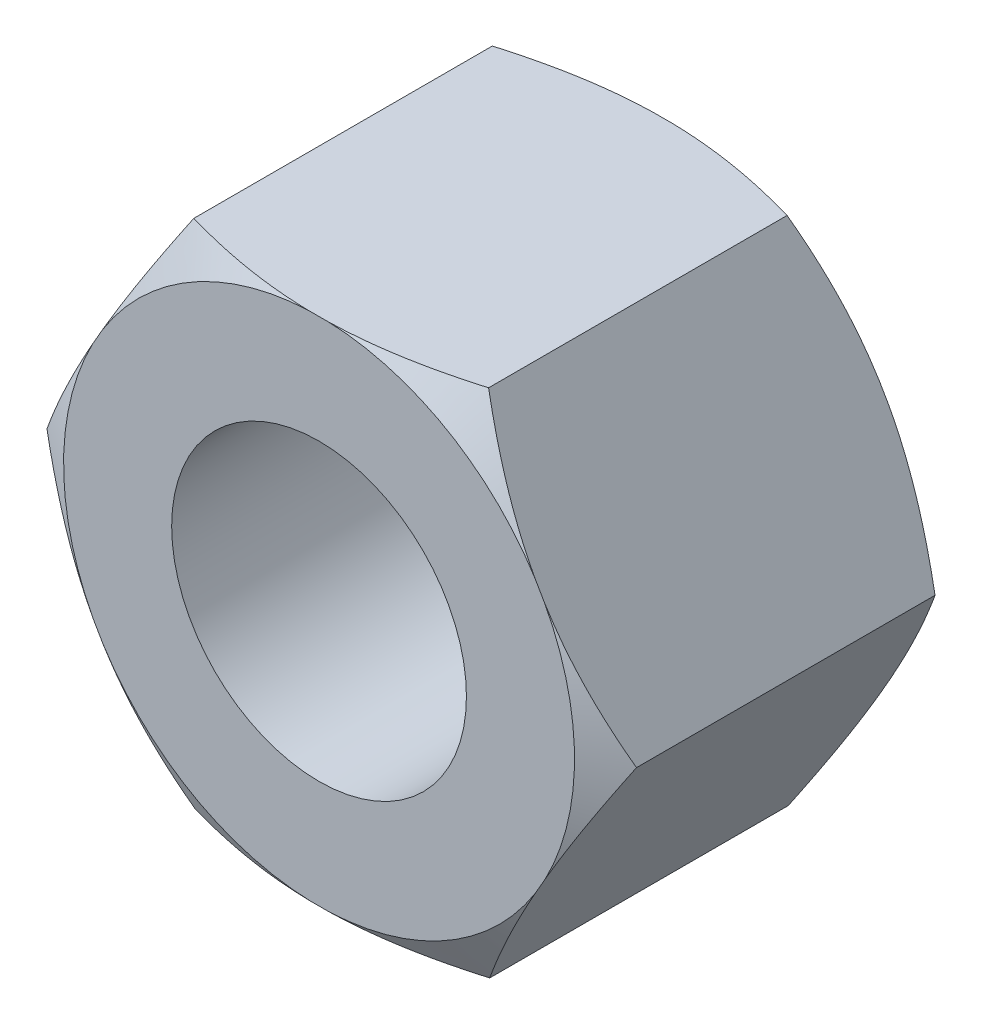
SolidWorks part; units mm, degrees
ref_plane "Front Plane" through (0, 0, 0) normal (0, 0, 1) x (1, 0, 0)
ref_plane "Top Plane" through (0, 0, 0) normal (0, 1, 0) x (1, 0, 0)
ref_plane "Right Plane" through (0, 0, 0) normal (1, 0, 0) x (0, 0, -1)
sketch "Sketch1" plane through (0, 0, 0) normal (0, 0, 1) x (1, 0, 0)
  line L1 (14.9435, 26.0134) -> (-15.0565, 25.9481)
  line L2 (-15.0565, 25.9481) -> (-30, -0.0653)
  line L3 (-30, -0.0653) -> (-14.9435, -26.0134)
  line L4 (-14.9435, -26.0134) -> (15.0565, -25.9481)
  line L5 (15.0565, -25.9481) -> (30, 0.0653)
  line L6 (30, 0.0653) -> (14.9435, 26.0134)
  circle A0 centre (0, 0) radius 25.9808 construction
  circle A1 centre (0, 0) radius 15
  dimension "D2" = 30
  dimension "D3" = 30
extrude "Boss-Extrude1" add sketch "Sketch1" along normal blind 35
sketch "Sketch3" plane through (0, 0, 0) normal (0, 0, -1) x (-1, 0, 0)
  circle A0 centre (0, 0) radius 26
  dimension "D1" = 52
extrude "Cut-Extrude1" cut sketch "Sketch3" against normal blind 35 draft 60 flip side to cut
sketch "Sketch4" plane through (0, 0, 35) normal (0, 0, 1) x (1, 0, 0)
  circle A0 centre (0, 0) radius 26
  dimension "D1" = 52
extrude "Cut-Extrude2" cut sketch "Sketch4" against normal blind 35 draft 60 flip side to cut
